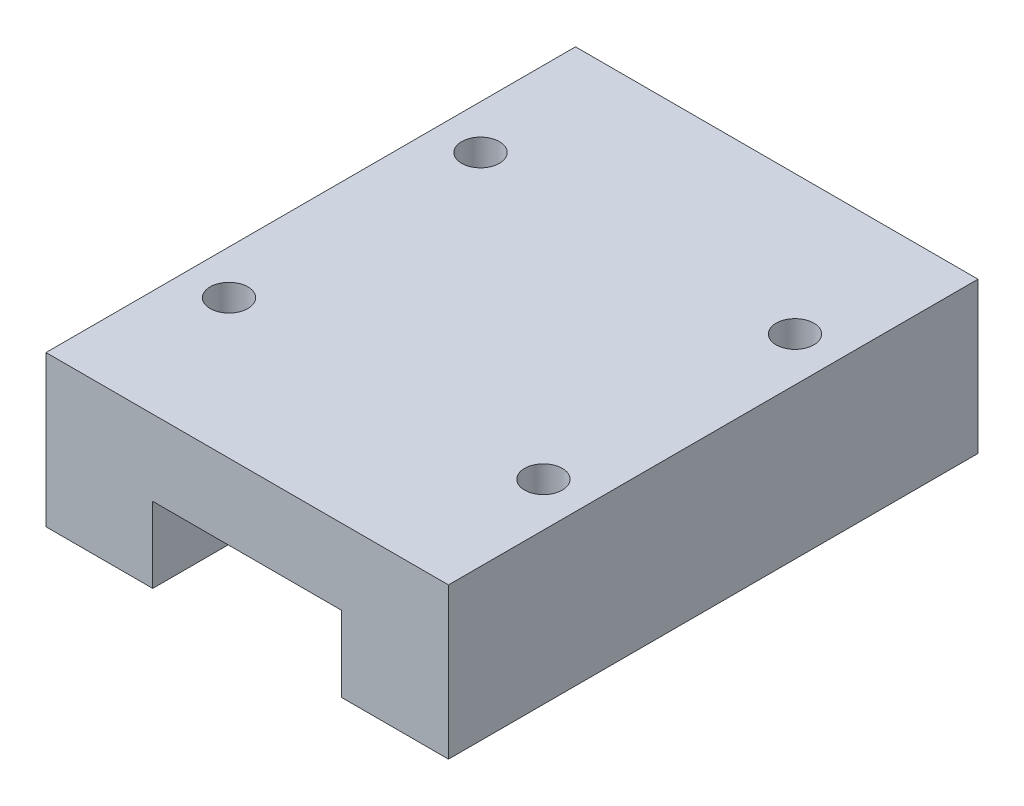
SolidWorks part; units mm, degrees
ref_plane "Front Plane" through (0, 0, 0) normal (0, 0, 1) x (1, 0, 0)
ref_plane "Top Plane" through (0, 0, 0) normal (0, 1, 0) x (1, 0, 0)
ref_plane "Right Plane" through (0, 0, 0) normal (1, 0, 0) x (0, 0, -1)
sketch "Sketch1" plane through (0, 0, 0) normal (0, 0, 1) x (1, 0, 0)
  line L1 (16, -6) -> (-16, -6)
  line L2 (16, -6) -> (16, 6)
  line L3 (16, 6) -> (-16, 6)
  line L4 (-16, -6) -> (-16, 6)
  line L5 (16, -6) -> (-16, 6) construction
  line L6 (16, 6) -> (-16, -6) construction
  point P0 (0, 0)
  dimension "D1" = 32
  dimension "D2" = 12
extrude "Boss-Extrude1" add sketch "Sketch1" along normal mid plane 42.1
sketch "Sketch2" plane through (0, 0, 21.05) normal (0, 0, 1) x (1, 0, 0)
  line L0 (-1001.4858, 0) -> (48998.5142, 0) construction
  line L1 (-7.5, -1003.4811) -> (-7.5, 48996.5189) construction
  line L2 (7.5, -1003.0566) -> (7.5, 48996.9434) construction
  line L3 (0, -1000) -> (0, 49000) construction
  line L4 (-16, -6) -> (16, -6) construction
  line L6 (-7.5141, 0) -> (7.5, 0)
  line L7 (-7.5141, 0) -> (-7.5141, -6)
  line L8 (-7.5141, -6) -> (7.5, -6)
  line L9 (7.5, 0) -> (7.5, -6)
  dimension "D1" = 7.5
  dimension "D2" = 7.5
  dimension "D3" = 6
extrude "Cut-Extrude1" cut sketch "Sketch2" against normal through all
sketch "Sketch3" plane through (0, 6, 0) normal (0, 1, 0) x (1, 0, 0)
  line L1 (-12.5, -10) -> (12.5, -10) construction
  line L2 (-12.5, -10) -> (-12.5, 10) construction
  line L3 (-12.5, 10) -> (12.5, 10) construction
  line L4 (12.5, -10) -> (12.5, 10) construction
  line L5 (-12.5, -10) -> (12.5, 10) construction
  line L6 (-12.5, 10) -> (12.5, -10) construction
  circle A0 centre (-12.5, 10) radius 1.5
  circle A1 centre (12.5, 10) radius 1.5
  circle A2 centre (12.5, -10) radius 1.5
  circle A3 centre (-12.5, -10) radius 1.5
  point P0 (0, 0)
  dimension "D3" = 3
  dimension "D4" = 3
  dimension "D5" = 3
  dimension "D6" = 3
  dimension "D1" = 25
  dimension "D2" = 20
extrude "Cut-Extrude2" cut sketch "Sketch3" against normal blind 6
